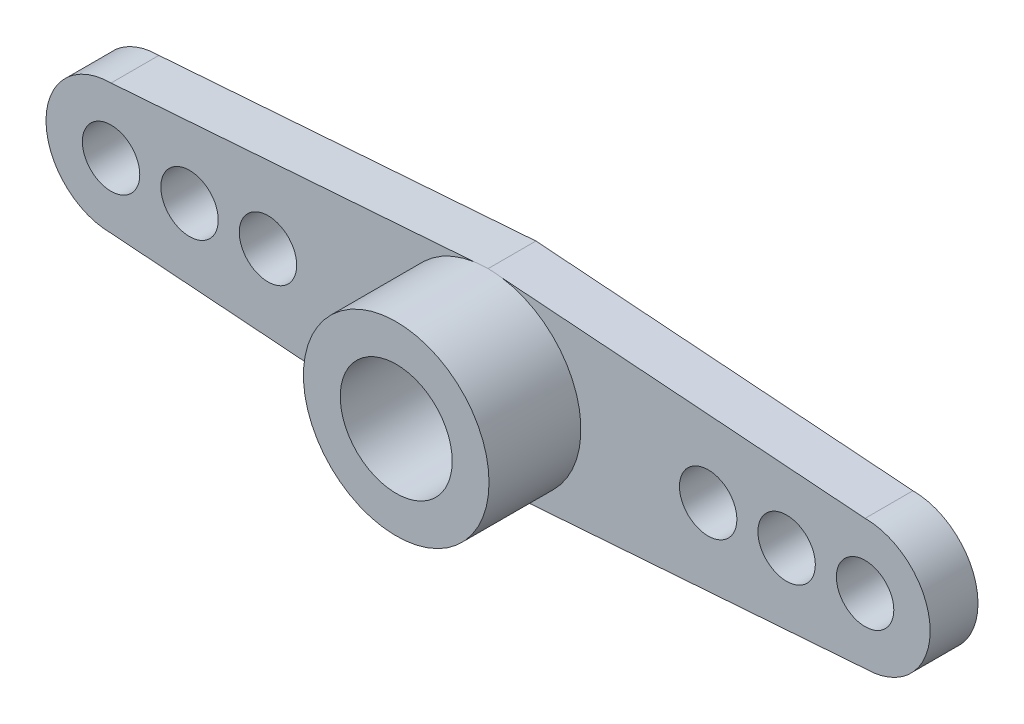
SolidWorks part; units mm, degrees
ref_plane "前视基准面" through (0, 0, 0) normal (0, 0, 1) x (1, 0, 0)
ref_plane "上视基准面" through (0, 0, 0) normal (0, 1, 0) x (1, 0, 0)
ref_plane "右视基准面" through (0, 0, 0) normal (1, 0, 0) x (0, 0, -1)
sketch "草图1" plane through (0, 0, 0) normal (0, 0, 1) x (1, 0, 0)
  line L1 (-19.7, 3.4) -> (0, 4.85)
  line L2 (0, 4.85) -> (19.7, 3.4)
  line L3 (-19.7, -3.4) -> (0, -4.85)
  line L4 (0, -4.85) -> (19.7, -3.4)
  circle A0 centre (0, 0) radius 3
  circle A1 centre (0, 0) radius 4.85
  circle A2 centre (19.7, 0) radius 1.5
  circle A3 centre (-19.7, 0) radius 1.5
  circle A4 centre (15.6, 0) radius 1.5
  circle A5 centre (11.5, 0) radius 1.5
  circle A6 centre (-15.6, 0) radius 1.5
  circle A7 centre (-11.5, 0) radius 1.5
  arc A8 (-19.7, 3.4) -> (-19.7, -3.4) centre (-19.7, 0) ccw
  arc A9 (19.7, -3.4) -> (19.7, 3.4) centre (19.7, 0) ccw
  point P7 (0, 0)
  dimension "D1" = 6
  dimension "D2" = 9.7
  dimension "D3" = 3
  dimension "D4" = 3
  dimension "D6" = 3
  dimension "D8" = 3
  dimension "D9" = 3
  dimension "D10" = 3
  dimension "D13" = 6.8
  dimension "D14" = 6.8
  dimension "D15" = 3
  dimension "D16" = 3
  dimension "D5" = 4.1
  dimension "D7" = 4.1
  dimension "D11" = 4.1
  dimension "D12" = 4.1
  dimension "D17" = 19.7
  dimension "D18" = 19.7
extrude "凸台-拉伸1" add sketch "草图1" along normal blind 2.5 contours L1 A8 L3 A1 A3 A6 A7 | L4 A9 L2 A1 A2 A4 A5 | L1 A1 L3 L4 L2 A0
sketch "草图2" plane through (0, 0, 2.5) normal (0, 0, 1) x (1, 0, 0)
  circle A0 centre (0, 0) radius 4.85
extrude "凸台-拉伸2" add sketch "草图2" along normal blind 4.8
sketch "草图3" plane through (0, 0, 7.3) normal (0, 0, 1) x (1, 0, 0)
  circle A0 centre (0, 0) radius 2.925
  dimension "D1" = 5.85
extrude "切除-拉伸1" cut sketch "草图3" against normal blind 4.5
sketch "草图4" plane through (0, 0, 2.5) normal (0, 0, -1) x (-1, 0, 0)
  circle A0 centre (0, 0) radius 1.5
  dimension "D1" = 3
extrude "切除-拉伸2" cut sketch "草图4" against normal blind 4.5
